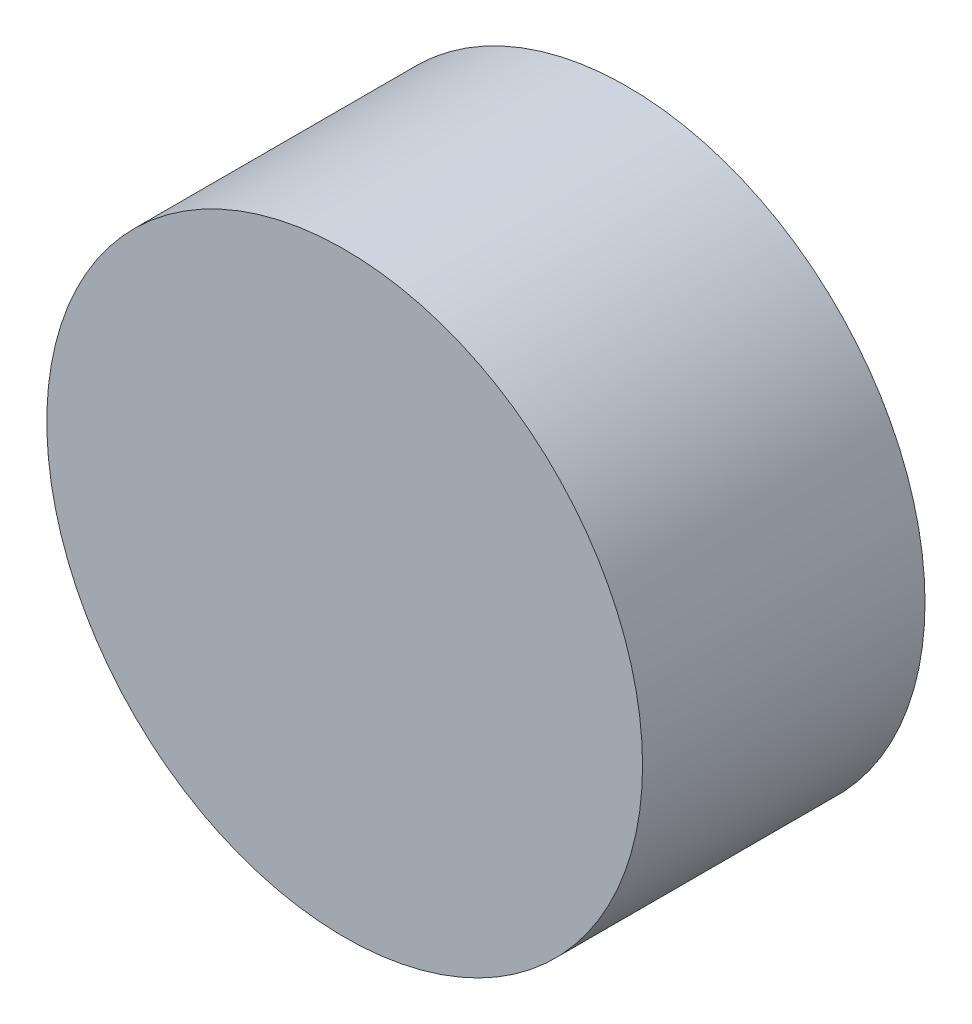
SolidWorks part; units mm, degrees
ref_plane "前视基准面" through (0, 0, 0) normal (0, 0, 1) x (1, 0, 0)
ref_plane "上视基准面" through (0, 0, 0) normal (0, 1, 0) x (1, 0, 0)
ref_plane "右视基准面" through (0, 0, 0) normal (1, 0, 0) x (0, 0, -1)
other "Configuration Table"
sketch "草图1" plane through (0, 0, 0) normal (0, 0, 1) x (1, 0, 0)
  circle A0 centre (0, 0) radius 29
  dimension "D1" = 58
extrude "凸台-拉伸1" add sketch "草图1" along normal blind 27.5
